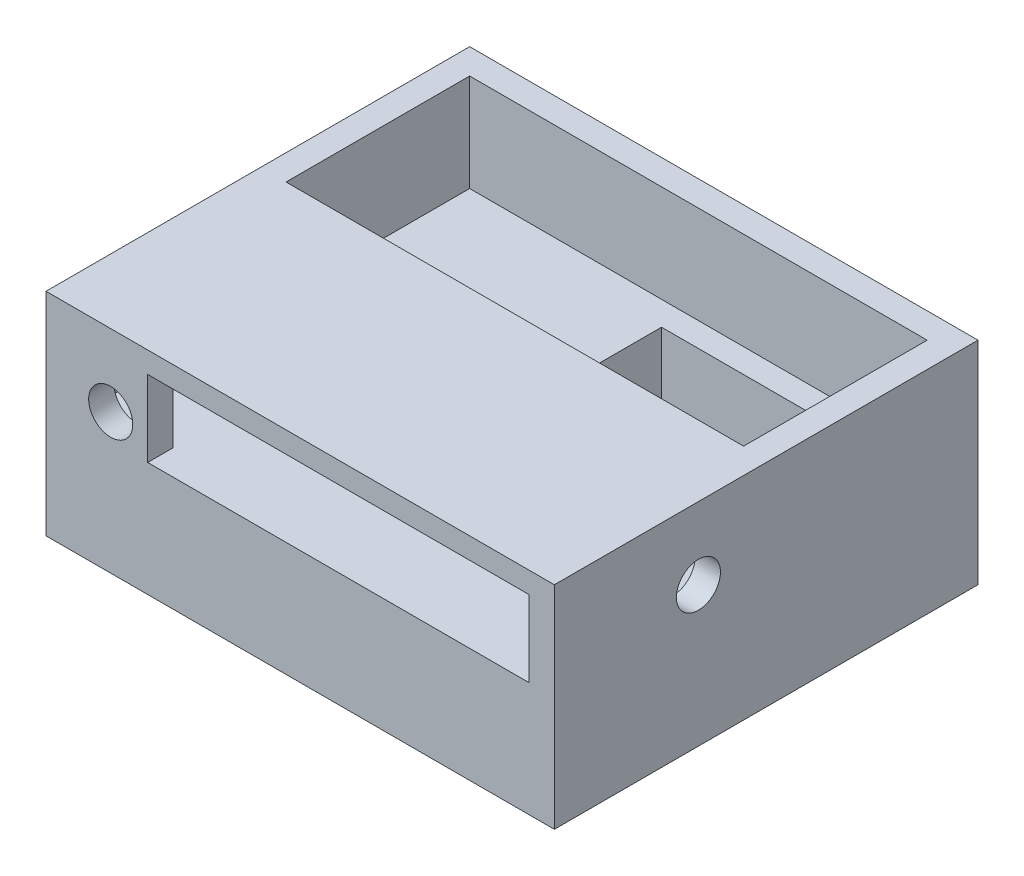
SolidWorks part; units mm, degrees
ref_plane "Plan de face" through (0, 0, 0) normal (0, 0, 1) x (1, 0, 0)
ref_plane "Plan de dessus" through (0, 0, 0) normal (0, 1, 0) x (1, 0, 0)
ref_plane "Plan de droite" through (0, 0, 0) normal (1, 0, 0) x (0, 0, -1)
sketch "Esquisse1" plane through (0, 0, 0) normal (0, 1, 0) x (1, 0, 0)
  line L1 (0, 0) -> (60, 0)
  line L2 (0, 0) -> (0, -50)
  line L3 (0, -50) -> (60, -50)
  line L4 (60, 0) -> (60, -50)
  dimension "D1" = 60
  dimension "D2" = 50
extrude "Boss.-Extru.1" add sketch "Esquisse1" along normal blind 20
sketch "Esquisse2" plane through (0, 20, 0) normal (0, 1, 0) x (1, 0, 0)
  line L0 (0, 0) -> (0, -50) construction
  line L1 (3, -3) -> (57, -3)
  line L2 (3, -3) -> (3, -47)
  line L3 (3, -47) -> (57, -47)
  line L4 (57, -3) -> (57, -47)
  line L5 (60, -50) -> (60, 0) construction
  line L6 (60, 0) -> (0, 0) construction
  line L7 (0, -50) -> (60, -50) construction
  dimension "D1" = 3
  dimension "D2" = 3
  dimension "D3" = 3
  dimension "D4" = 3
extrude "Enlèv. mat.-Extru.1" cut sketch "Esquisse2" against normal blind 11.5
sketch "Esquisse3" plane through (0, 8.5, 0) normal (0, 1, 0) x (1, 0, 0)
  line L0 (3, -25) -> (57, -25) construction
  line L1 (28.5, -5.85) -> (51.5, -5.85)
  line L2 (28.5, -5.85) -> (28.5, -18.15)
  line L3 (28.5, -18.15) -> (51.5, -18.15)
  line L4 (51.5, -5.85) -> (51.5, -18.15)
  line L5 (3, -3) -> (3, -47) construction
  line L6 (57, -47) -> (57, -3) construction
  line L7 (30, -3) -> (30, -47) construction
  line L8 (57, -3) -> (3, -3) construction
  line L9 (3, -47) -> (57, -47) construction
  line L10 (28.5, -12) -> (51.5, -12) construction
  line L11 (40, -5.85) -> (40, -18.15) construction
  dimension "D1" = 10
  dimension "D2" = 23
  dimension "D3" = 12.3
  dimension "D4" = 13
extrude "Enlèv. mat.-Extru.2" cut sketch "Esquisse3" against normal up to next
sketch "Esquisse4" plane through (60, 0, 0) normal (1, 0, 0) x (0, 0, -1)
  line L0 (-50, 10) -> (0, 10) construction
  line L1 (-50, 20) -> (-50, 0) construction
  line L2 (0, 20) -> (0, 0) construction
  line L3 (-25, 20) -> (-25, 0) construction
  line L4 (-50, 20) -> (0, 20) construction
  line L5 (-50, 0) -> (0, 0) construction
  circle A0 centre (-33, 11.5) radius 2.6
  point P14 (-31.5605, 11.5)
  dimension "D1" = 5.2
  dimension "D2" = 1.5
  dimension "D3" = 8
extrude "Enlèv. mat.-Extru.3" cut sketch "Esquisse4" against normal blind 10
sketch "Esquisse5" plane through (0, 0, 0) normal (0, -1, 0) x (1, 0, 0)
  line L0 (28.5, 5.85) -> (51.5, 5.85) construction
  line L1 (60, 0) -> (0, 0)
  line L2 (60, 0) -> (60, 50)
  line L3 (60, 50) -> (0, 50)
  line L4 (0, 0) -> (0, 50)
  line L5 (56.5, 5.85) -> (23.5, 5.85)
  line L6 (56.5, 5.85) -> (56.5, 18.15)
  line L7 (56.5, 18.15) -> (23.5, 18.15)
  line L8 (23.5, 5.85) -> (23.5, 18.15)
  line L9 (51.5, 18.15) -> (28.5, 18.15) construction
  line L10 (51.5, 5.85) -> (51.5, 18.15) construction
  line L11 (28.5, 18.15) -> (28.5, 5.85) construction
  dimension "D1" = 5
  dimension "D2" = 5
extrude "Boss.-Extru.2" add sketch "Esquisse5" along normal blind 5
sketch "Esquisse6" plane through (0, 0, 50) normal (0, 0, 1) x (1, 0, 0)
  circle A0 centre (7.6363, 11.4923) radius 2.6
  point P2 (7.6137, 10.2013)
  point P3 (0, 0)
  point P4 (7.6875, 10.9871)
  point P5 (0, 0)
  point P6 (7.6363, 11.4923)
  dimension "D1" = 5.2
extrude "Enlèv. mat.-Extru.4" cut sketch "Esquisse6" against normal blind 10
sketch "Esquisse8" plane through (0, 20, 0) normal (0, 1, 0) x (1, 0, 0)
  line L0 (0, -50) -> (60, -50) construction
  line L1 (0, -50) -> (60, -50)
  line L2 (0, -50) -> (0, -24.6679)
  line L3 (0, -24.6679) -> (60, -24.6679)
  line L4 (60, -50) -> (60, -24.6679)
  line L5 (60, -50) -> (60, 0) construction
extrude "Boss.-Extru.3" add sketch "Esquisse8" against normal blind 2.5
sketch "Esquisse9" plane through (0, 0, 50) normal (0, 0, 1) x (1, 0, 0)
  line L1 (57, 17.5) -> (12, 17.5)
  line L2 (57, 17.5) -> (57, 8.5)
  line L3 (57, 8.5) -> (12, 8.5)
  line L4 (12, 17.5) -> (12, 8.5)
  line L5 (0, 20) -> (60, 20) construction
  line L6 (60, 20) -> (60, -5) construction
  point P8 (0, 0)
  dimension "D1" = 2.5
  dimension "D2" = 45
  dimension "D3" = 3
  dimension "D4" = 9
extrude "Enlèv. mat.-Extru.6" cut sketch "Esquisse9" against normal blind 3
